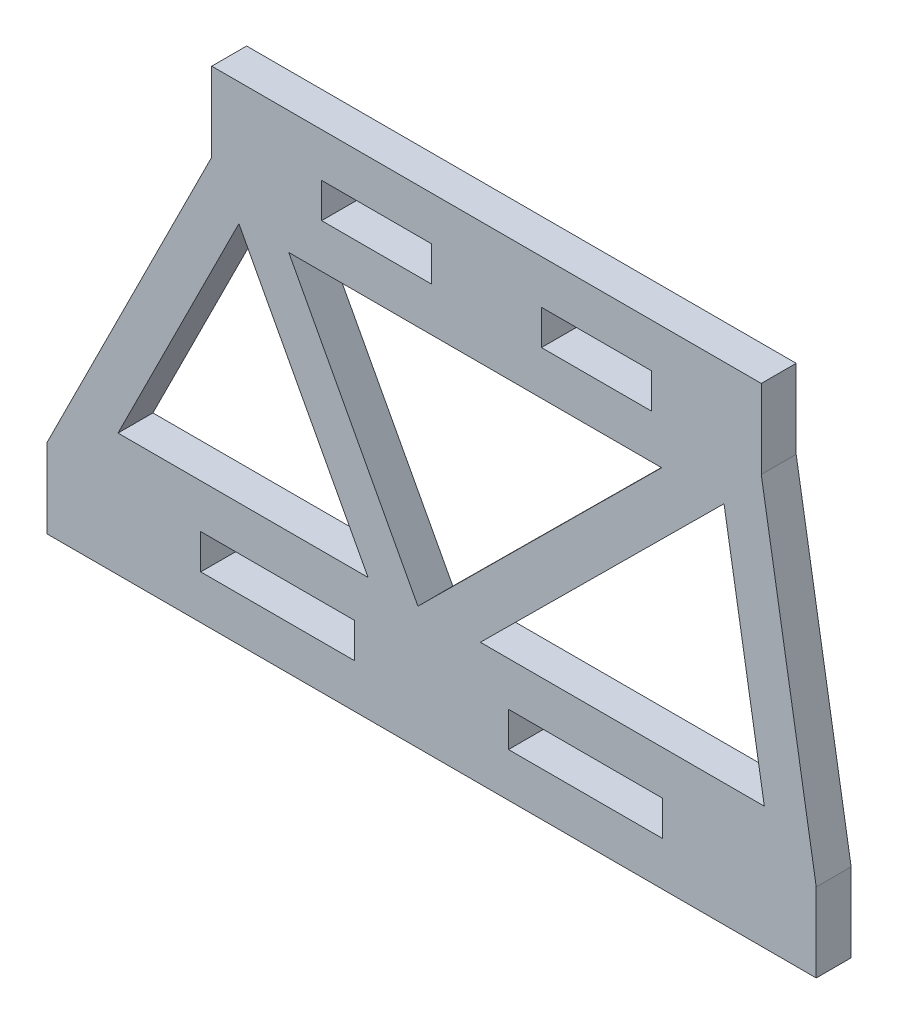
SolidWorks part; units mm, degrees
material "Mahogany"
ref_plane "Front Plane" through (0, 0, 0) normal (0, 0, 1) x (1, 0, 0)
ref_plane "Top Plane" through (0, 0, 0) normal (0, 1, 0) x (1, 0, 0)
ref_plane "Right Plane" through (0, 0, 0) normal (1, 0, 0) x (0, 0, -1)
sketch "Sketch1" plane through (0, 0, 0) normal (0, 0, 1) x (1, 0, 0)
  line L0 (0, 0) -> (70, 0) construction
  line L1 (15, 30) -> (65, 30) construction
  line L2 (15, 30) -> (0, 0)
  line L3 (65, 30) -> (70, 0)
  line L4 (0, 0) -> (0, -7.175)
  line L5 (0, -7.175) -> (70, -7.175)
  line L6 (70, -7.175) -> (70, 0)
  line L7 (15, 30) -> (15, 37.175)
  line L8 (15, 37.175) -> (65, 37.175)
  line L9 (65, 37.175) -> (65, 30)
  line L10 (25, 30) -> (25, 33.175)
  line L11 (25, 33.175) -> (35, 33.175)
  line L12 (35, 33.175) -> (35, 30)
  line L13 (14, 0) -> (14, -3.175)
  line L14 (14, -3.175) -> (28, -3.175)
  line L15 (28, -3.175) -> (28, 0)
  line L16 (28, 0) -> (14, 0)
  line L17 (25, 30) -> (35, 30)
  line L18 (45, 33.175) -> (55, 33.175)
  line L19 (45, 30) -> (45, 33.175)
  line L20 (45, 30) -> (55, 30)
  line L21 (55, 33.175) -> (55, 30)
  line L22 (42, 0) -> (42, -3.175)
  line L23 (56, 0) -> (42, 0)
  line L24 (56, -3.175) -> (56, 0)
  line L25 (42, -3.175) -> (56, -3.175)
  point P17 (65, 33.5875)
  point P23 (42, -1.5875)
  dimension "D1" = 70
  dimension "D2" = 3.175
  dimension "D3" = 4
  dimension "D4" = 10
  dimension "D7" = 10
  dimension "D11" = 14
  dimension "D12" = 14
  dimension "D13" = 14
  dimension "D14" = 3.175
  dimension "D15" = 4
  dimension "D9" = 10
  dimension "D16" = 30
  dimension "D5" = 65
  dimension "D6" = 55
  dimension "D17" = 15
  dimension "D18" = 50
  dimension "D19" = 5
  dimension "D8" = 2
  dimension "D10" = 2
extrude "Boss-Extrude1" add sketch "Sketch1" along normal blind 3.175
sketch "Sketch2" plane through (0, 0, 0) normal (0, 0, 1) x (1, 0, 0)
  line L0 (61.6115, 26) -> (65.2782, 4)
  line L1 (65.2782, 4) -> (39.4404, 4)
  line L2 (39.4404, 4) -> (61.6115, 26)
  line L3 (55.9326, 26) -> (33.7615, 4)
  line L4 (33.7615, 4) -> (22.0073, 26)
  line L5 (22.0073, 26) -> (55.9326, 26)
  line L6 (17.4721, 26) -> (6.4721, 4)
  line L7 (6.4721, 4) -> (29.2264, 4)
  line L8 (29.2264, 4) -> (17.4721, 26)
  line L9 (61.6115, 26) -> (55.9326, 26) construction
  line L10 (22.0073, 26) -> (17.4721, 26) construction
  line L11 (39.4404, 4) -> (33.7615, 4) construction
  line L12 (29.2264, 4) -> (33.7615, 4) construction
  line L13 (70, 0) -> (65, 30) construction
  line L14 (15, 30) -> (0, 0) construction
  line L15 (56, 0) -> (42, 0) construction
  line L16 (45, 30) -> (55, 30) construction
  point P17 (23.3492, 15)
  dimension "D3" = 4
  dimension "D1" = 4
  dimension "D2" = 4
  dimension "D4" = 4
  dimension "D5" = 4
  dimension "D6" = 4
extrude "Cut-Extrude1" cut sketch "Sketch2" along normal up to next
equation "\"T\"= 0.125in'Material Thickness"
equation "\"L_f\"= 20mm'Length of front platform"
equation "\"L_m\"= 70mm'Lenght of mid platform"
equation "\"L_b\"= 20mm'Length of back platform"
equation "\"L_f_t\"= 5mm'Length of front indent on top"
equation "\"L_b_t\"= 15mm'Length of back indent on top"
equation "\"L_m_t\"= \"L_m\" - \"L_b_t\" - \"L_f_t\"'Length of top platform"
equation "\"W\"= 45mm'Width of basket"
equation "\"H\"= 30mm'Height of basket"
equation "\"W_min\"= round ( 1.25 * \"T\" )'Minimum width of parts"
equation "\"D1@Sketch1\"=\"L_m\""
equation "\"D2@Sketch1\"=\"T\""
equation "\"D3@Sketch1\"=\"W_min\""
equation "\"D4@Sketch1\"=\"L_m_t\"/5"
equation "\"D7@Sketch1\"=\"L_m_t\"/5"
equation "\"D12@Sketch1\"=\"L_m\"/5"
equation "\"D11@Sketch1\"=\"L_m\"/5"
equation "\"D13@Sketch1\"=\"L_m\"/5"
equation "\"D14@Sketch1\"=\"T\""
equation "\"D15@Sketch1\"=\"W_min\""
equation "\"D1@Boss-Extrude1\"=\"T\""
equation "\"D1@Sketch2\"=\"W_min\""
equation "\"D2@Sketch2\"=\"W_min\""
equation "\"D3@Sketch2\"=\"W_min\""
equation "\"D4@Sketch2\"=\"W_min\""
equation "\"D5@Sketch2\"=\"W_min\""
equation "\"D6@Sketch2\"=\"W_min\""
equation "\"D9@Sketch1\"=\"L_m_t\"/5"
equation "\"D16@Sketch1\"=\"H\""
equation "\"D5@Sketch1\"=\"L_m_t\"+\"L_b_t\""
equation "\"D6@Sketch1\"=\"L_m_t\"+\"L_f_t\""
